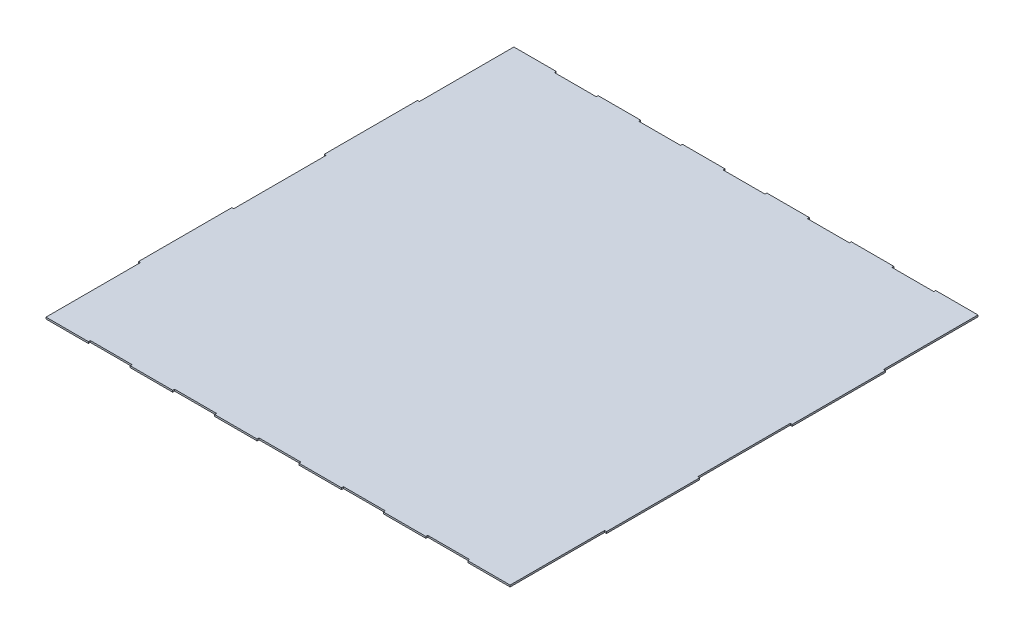
SolidWorks part; units mm, degrees
ref_plane "Front Plane" through (0, 0, 0) normal (0, 0, 1) x (1, 0, 0)
ref_plane "Top Plane" through (0, 0, 0) normal (0, 1, 0) x (1, 0, 0)
ref_plane "Right Plane" through (0, 0, 0) normal (1, 0, 0) x (0, 0, -1)
sketch "oneSide" plane through (0, 0, 0) normal (0, 1, 0) x (1, 0, 0)
  line L0 (-216.6667, 216.6667) -> (-216.6667, 218.4267)
  line L1 (-177.1127, 216.6667) -> (-138.0388, 216.6667)
  line L2 (-218.4267, 130.16) -> (-218.4267, 43.1733)
  line L4 (216.6667, 216.6667) -> (216.6667, 130.16)
  line L5 (-216.6667, 218.4267) -> (-177.1127, 218.4267)
  line L6 (-177.1127, 218.4267) -> (-177.1127, 216.6667)
  line L7 (-98.3248, 216.6667) -> (-59.2509, 216.6667)
  line L8 (-138.0388, 218.4267) -> (-98.3248, 218.4267)
  line L9 (-138.0388, 218.4267) -> (-138.0388, 216.6667)
  line L10 (-19.537, 216.6667) -> (19.537, 216.6667)
  line L11 (-98.3248, 218.4267) -> (-98.3248, 216.6667)
  line L12 (-59.2509, 218.4267) -> (-19.537, 218.4267)
  line L13 (-59.2509, 218.4267) -> (-59.2509, 216.6667)
  line L14 (59.2509, 216.6667) -> (98.3248, 216.6667)
  line L15 (-19.537, 218.4267) -> (-19.537, 216.6667)
  line L16 (19.537, 218.4267) -> (59.2509, 218.4267)
  line L17 (19.537, 218.4267) -> (19.537, 216.6667)
  line L18 (138.0388, 216.6667) -> (177.1127, 216.6667)
  line L19 (59.2509, 218.4267) -> (59.2509, 216.6667)
  line L20 (98.3248, 218.4267) -> (138.0388, 218.4267)
  line L21 (98.3248, 218.4267) -> (98.3248, 216.6667)
  line L22 (216.6667, 0) -> (-216.6667, 0)
  line L23 (138.0388, 218.4267) -> (138.0388, 216.6667)
  line L24 (177.1127, 218.4267) -> (216.6667, 218.4267)
  line L25 (177.1127, 218.4267) -> (177.1127, 216.6667)
  line L26 (216.6667, 43.1733) -> (216.6667, 0)
  line L27 (216.6667, 218.4267) -> (216.6667, 216.6667)
  line L28 (218.4267, 130.16) -> (216.6667, 130.16)
  line L29 (-218.4267, 130.16) -> (-216.6667, 130.16)
  line L30 (-216.6667, 216.6667) -> (-216.6667, 130.16)
  line L31 (-218.4267, 43.1733) -> (-216.6667, 43.1733)
  line L32 (218.4267, 130.16) -> (218.4267, 43.1733)
  line L33 (218.4267, 43.1733) -> (216.6667, 43.1733)
  line L34 (-216.6667, 43.1733) -> (-216.6667, 0)
  point P5 (0, 0)
  dimension "D1" = 433.3333
  dimension "D3" = 1.76
  dimension "D2" = 216.6667
  dimension "D4" = 86.5067
  dimension "D5" = 86.9867
  dimension "D6" = 39.5539
  dimension "D7" = 39.7139
  dimension "D8" = 39.0739
extrude "Boss-Extrude1" add sketch "oneSide" along normal blind 1.6
mirror "Mirror1" about plane through (216.6667, 1.6, 0) normal (0, 0, -1) of "Boss-Extrude1"
equation "\"thinkness\"= \"epaisseur\""
equation "\"D3@oneSide\" = \"thinkness\" + \"jeu\""
equation "\"D1@Boss-Extrude1\"= \"thinkness\""
equation "\"D4@oneSide\" = \"largeur\" / 5 - \"jeu\""
equation "\"largeur\"= \"nbCarre\" * \"Coté\""
equation "\"D2@oneSide\"= \"largeur\" / 2mm"
equation "\"D5@oneSide\"= \"largeur\" / 5 + \"jeu\" * 2"
equation "\"hauteur\"= 47.5"
equation "\"longueur\"= \"nbCarre\" * \"Coté\""
equation "\"D1@oneSide\"= \"longueur\""
equation "\"jeu\"= 0.16"
equation "\"D6@oneSide\"= \"longueur\" / 11 + \"jeu\""
equation "\"D7@oneSide\"= \"longueur\" / 11 + \"jeu\" * 2"
equation "\"D8@oneSide\"= \"longueur\" / 11 - \"jeu\" * 2"
equation "\"Coté\"= 33.333333"
equation "\"nbCarre\"= 13"
equation "\"epaisseur\"= 1.6"
equation "\"rapportEncoche\"= 0.5"
